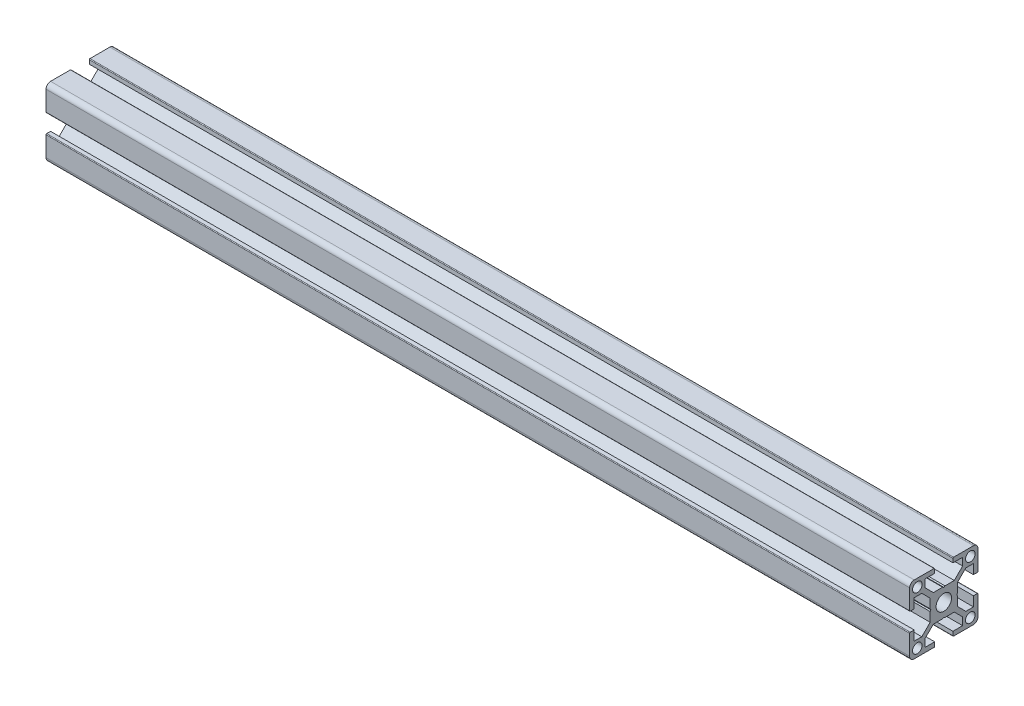
SolidWorks part; units mm, degrees
ref_plane "Front Plane" through (0, 0, 0) normal (0, 0, 1) x (1, 0, 0)
ref_plane "Top Plane" through (0, 0, 0) normal (0, 1, 0) x (1, 0, 0)
ref_plane "Right Plane" through (0, 0, 0) normal (1, 0, 0) x (0, 0, -1)
sketch "Sketch1" plane through (0, 0, 0) normal (0, 0, 1) x (1, 0, 0)
  line L0 (0, 0) -> (379, 0)
  dimension "D1" = 379
other "30xs6 30X30S6(1)"
ref_plane "Plane1" through (0, 0, 0) normal (1, 0, 0) x (0, 1, 0)
sketch "草图1" plane through (0, 0, 0) normal (1, 0, 0) x (0, 1, 0)
  line L0 (-14.7, 4) -> (-13, 4)
  line L1 (-13, 4) -> (-13, 8.25)
  line L2 (-13, 8.25) -> (-9.6642, 8.25)
  line L3 (-9.6642, 8.25) -> (-6, 4.5858)
  line L4 (-6, 4.5858) -> (-6, 0.5196)
  line L5 (-6, 0.5196) -> (-5.7, 0)
  line L6 (-5.7, 0) -> (-6, -0.5196)
  line L7 (-6, -0.5196) -> (-6, -4.5858)
  line L8 (-6, -4.5858) -> (-9.6642, -8.25)
  line L9 (-9.6642, -8.25) -> (-13, -8.25)
  line L10 (-13, -8.25) -> (-13, -4)
  line L11 (-13, -4) -> (-14.7, -4)
  line L12 (-15, -4.3) -> (-15, -13)
  line L13 (-13, -15) -> (-4.3, -15)
  line L14 (-4, -14.7) -> (-4, -13)
  line L15 (-4, -13) -> (-8.25, -13)
  line L16 (-8.25, -13) -> (-8.25, -9.6642)
  line L17 (-8.25, -9.6642) -> (-4.5858, -6)
  line L18 (-4.5858, -6) -> (-0.5196, -6)
  line L19 (-0.5196, -6) -> (0, -5.7)
  line L20 (0, -5.7) -> (0.5196, -6)
  line L21 (0.5196, -6) -> (4.5858, -6)
  line L22 (4.5858, -6) -> (8.25, -9.6642)
  line L23 (8.25, -9.6642) -> (8.25, -13)
  line L24 (8.25, -13) -> (4, -13)
  line L25 (4, -13) -> (4, -14.7)
  line L26 (4.3, -15) -> (13, -15)
  line L27 (15, -13) -> (15, -4.3)
  line L28 (14.7, -4) -> (13, -4)
  line L29 (13, -4) -> (13, -8.25)
  line L30 (13, -8.25) -> (9.6642, -8.25)
  line L31 (9.6642, -8.25) -> (6, -4.5858)
  line L32 (6, -4.5858) -> (6, -0.5196)
  line L33 (6, -0.5196) -> (5.7, 0)
  line L34 (5.7, 0) -> (6, 0.5196)
  line L35 (6, 0.5196) -> (6, 4.5858)
  line L36 (6, 4.5858) -> (9.6642, 8.25)
  line L37 (9.6642, 8.25) -> (13, 8.25)
  line L38 (13, 8.25) -> (13, 4)
  line L39 (13, 4) -> (14.7, 4)
  line L40 (15, 4.3) -> (15, 13)
  line L41 (13, 15) -> (4.3, 15)
  line L42 (4, 14.7) -> (4, 13)
  line L43 (4, 13) -> (8.25, 13)
  line L44 (8.25, 13) -> (8.25, 9.6642)
  line L45 (8.25, 9.6642) -> (4.5858, 6)
  line L46 (4.5858, 6) -> (0.5196, 6)
  line L47 (0.5196, 6) -> (0, 5.7)
  line L48 (0, 5.7) -> (-0.5196, 6)
  line L49 (-0.5196, 6) -> (-4.5858, 6)
  line L50 (-4.5858, 6) -> (-8.25, 9.6642)
  line L51 (-8.25, 9.6642) -> (-8.25, 13)
  line L52 (-8.25, 13) -> (-4, 13)
  line L53 (-4, 13) -> (-4, 14.7)
  line L54 (-4.3, 15) -> (-13, 15)
  line L55 (-15, 13) -> (-15, 4.3)
  arc A0 (-15, 4.3) -> (-14.7, 4) centre (-14.7, 4.3) ccw
  arc A1 (-14.7, -4) -> (-15, -4.3) centre (-14.7, -4.3) ccw
  arc A2 (-15, -13) -> (-13, -15) centre (-13, -13) ccw
  arc A3 (-4.3, -15) -> (-4, -14.7) centre (-4.3, -14.7) ccw
  arc A4 (4, -14.7) -> (4.3, -15) centre (4.3, -14.7) ccw
  arc A5 (13, -15) -> (15, -13) centre (13, -13) ccw
  arc A6 (15, -4.3) -> (14.7, -4) centre (14.7, -4.3) ccw
  arc A7 (14.7, 4) -> (15, 4.3) centre (14.7, 4.3) ccw
  arc A8 (15, 13) -> (13, 15) centre (13, 13) ccw
  arc A9 (4.3, 15) -> (4, 14.7) centre (4.3, 14.7) ccw
  arc A10 (-4, 14.7) -> (-4.3, 15) centre (-4.3, 14.7) ccw
  arc A11 (-13, 15) -> (-15, 13) centre (-13, 13) ccw
  circle A12 centre (11.625, 11.625) radius 2.1
  circle A13 centre (11.625, -11.625) radius 2.1
  circle A14 centre (0, 0) radius 3.4
  circle A15 centre (-11.625, -11.625) radius 2.1
  circle A16 centre (-11.625, 11.625) radius 2.1
  point P90 (-15, 15)
  point P91 (-0.2598, 14.9121)
  point P92 (15, 15)
  point P93 (15, 0)
  point P94 (15, -15)
  point P95 (0.2598, -15)
  point P96 (-15, -15)
  point P97 (-15, 0)
  point P98 (0, 0)
